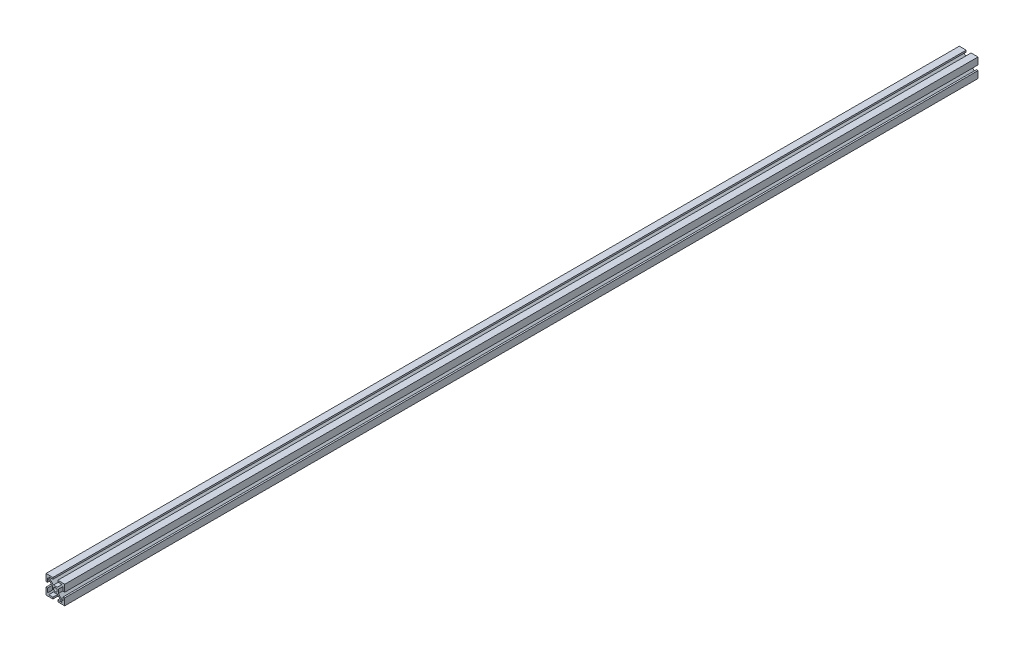
SolidWorks part; units mm, degrees
material "6063-T5"
ref_plane "Front Plane" through (0, 0, 0) normal (0, 0, 1) x (1, 0, 0)
ref_plane "Top Plane" through (0, 0, 0) normal (0, 1, 0) x (1, 0, 0)
ref_plane "Right Plane" through (0, 0, 0) normal (1, 0, 0) x (0, 0, -1)
sketch "Sketch1" plane through (0, 0, 0) normal (0, 0, 1) x (1, 0, 0)
  line L0 (0, 25) -> (25, 0) construction
  line L1 (0, 0) -> (25, 0) construction
  line L2 (0, 0) -> (0, 25) construction
  line L3 (0, 25) -> (25, 25) construction
  line L4 (25, 0) -> (25, 25) construction
  line L5 (25, 25) -> (0, 0) construction
  line L6 (22.86, 2.14) -> (22.86, 0) construction
  line L7 (2.14, 2.14) -> (22.86, 2.14) construction
  line L8 (2.14, 2.14) -> (2.14, 22.86) construction
  line L9 (2.14, 22.86) -> (22.86, 22.86) construction
  line L10 (22.86, 2.14) -> (22.86, 22.86) construction
  line L11 (22.86, 2.14) -> (25, 2.14) construction
  line L12 (8.45, 15.0368) -> (2.14, 21.3468)
  line L13 (16.55, 8.45) -> (8.45, 8.45) construction
  line L14 (16.55, 8.45) -> (16.55, 16.55) construction
  line L15 (16.55, 16.55) -> (8.45, 16.55) construction
  line L16 (8.45, 8.45) -> (8.45, 16.55) construction
  line L17 (9.9632, 16.55) -> (3.6532, 22.86)
  line L18 (3.6532, 22.86) -> (2.8966, 22.1034) construction
  line L19 (2.8966, 22.1034) -> (2.14, 21.3468) construction
  line L20 (8.45, 9.9632) -> (8.45, 15.0368)
  line L21 (15.0368, 16.55) -> (21.3468, 22.86)
  line L22 (21.3468, 22.86) -> (22.1034, 22.1034) construction
  line L23 (22.1034, 22.1034) -> (22.86, 21.3468) construction
  line L24 (22.86, 21.3468) -> (16.55, 15.0368)
  line L25 (16.55, 9.9632) -> (22.86, 3.6532)
  line L26 (22.86, 3.6532) -> (22.1034, 2.8966) construction
  line L27 (21.3468, 2.14) -> (15.0368, 8.45)
  line L28 (9.9632, 8.45) -> (3.6532, 2.14)
  line L29 (22.1034, 2.8966) -> (21.3468, 2.14) construction
  line L30 (2.14, 3.6532) -> (8.45, 9.9632)
  line L31 (3.6532, 2.14) -> (2.8966, 2.8966) construction
  line L32 (2.8966, 2.8966) -> (2.14, 3.6532) construction
  line L33 (9.9632, 16.55) -> (15.0368, 16.55)
  line L34 (16.55, 15.0368) -> (16.55, 9.9632)
  line L35 (16.55, 9.9632) -> (16.4545, 9.9275)
  line L36 (15.0368, 8.45) -> (9.9632, 8.45)
  line L37 (0, 12.5) -> (2.14, 12.5) construction
  line L38 (1.07, 15.75) -> (1.07, 12.5) construction
  line L39 (1.07, 12.5) -> (1.07, 9.25) construction
  line L40 (2.14, 15.75) -> (0, 15.75)
  line L41 (2.14, 9.25) -> (0, 9.25)
  line L42 (12.5, 2.14) -> (12.5, 0) construction
  line L43 (12.5, 1.07) -> (15.75, 1.07) construction
  line L44 (12.5, 1.07) -> (9.25, 1.07) construction
  line L45 (15.75, 0) -> (15.75, 2.14)
  line L46 (9.25, 2.14) -> (9.25, 0)
  line L47 (22.86, 15.75) -> (25, 15.75)
  line L48 (22.86, 9.25) -> (25, 9.25)
  line L49 (9.25, 25) -> (9.25, 22.86)
  line L50 (15.75, 25) -> (15.75, 22.86)
  line L51 (3.6532, 2.14) -> (9.25, 2.14)
  line L52 (15.75, 2.14) -> (21.3468, 2.14)
  line L53 (22.86, 9.25) -> (22.86, 3.6532)
  line L54 (22.86, 15.75) -> (22.86, 21.3468)
  line L55 (21.3468, 22.86) -> (15.75, 22.86)
  line L56 (9.25, 22.86) -> (3.6532, 22.86)
  line L57 (2.14, 21.3468) -> (2.14, 15.75)
  line L58 (2.14, 9.25) -> (2.14, 3.6532)
  line L59 (9.25, 0) -> (0, 0)
  line L60 (0, 0) -> (0, 9.25)
  line L61 (0, 15.75) -> (0, 25)
  line L62 (0, 25) -> (9.25, 25)
  line L63 (15.75, 25) -> (25, 25)
  line L64 (25, 25) -> (25, 15.75)
  line L65 (25, 9.25) -> (25, 0)
  line L66 (25, 0) -> (15.75, 0)
  circle A0 centre (12.5, 12.5) radius 2.5
  dimension "D2" = 5
  dimension "D6" = 6.5
  dimension "D1" = 25
  dimension "D3" = 2.14
  dimension "D4" = 4.05
  dimension "D5" = 2.14
  dimension "D7" = 6.5
extrude "Boss-Extrude1" add sketch "Sketch1" along normal blind 1220
